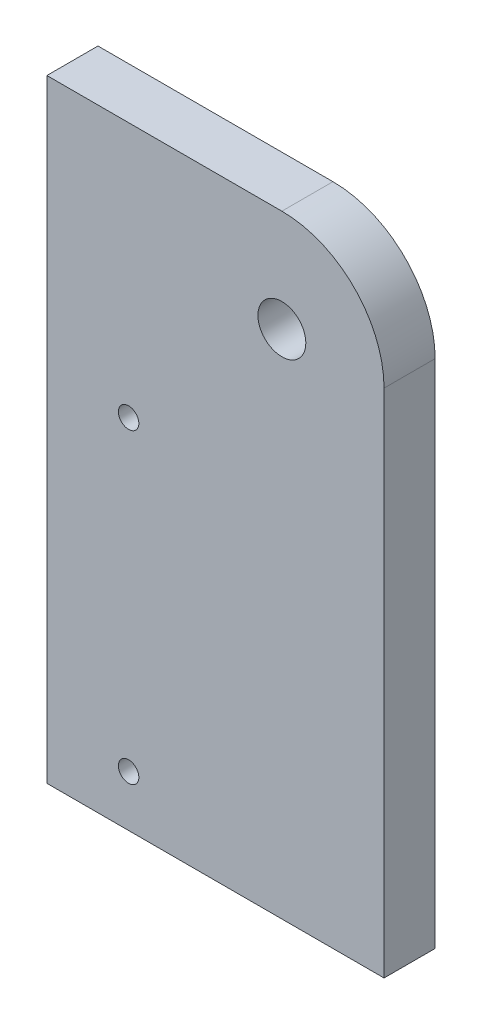
SolidWorks part; units mm, degrees
ref_plane "Alzado" through (0, 0, 0) normal (0, 0, 1) x (1, 0, 0)
ref_plane "Planta" through (0, 0, 0) normal (0, 1, 0) x (1, 0, 0)
ref_plane "Vista lateral" through (0, 0, 0) normal (1, 0, 0) x (0, 0, -1)
sketch "Croquis1" plane through (0, 0, 0) normal (0, 0, 1) x (1, 0, 0)
  line L0 (37.0022, 58.5355) -> (37.0385, 58.5355)
  line L1 (0, 0) -> (33, 0)
  line L2 (0, 0) -> (0, 60)
  line L3 (0, 60) -> (33, 60)
  line L4 (33, 0) -> (33, 60)
  line L5 (33, 60) -> (23, 60)
  line L6 (33, 60) -> (33, 50)
  line L7 (33, 50) -> (23, 50)
  line L8 (23, 60) -> (23, 50)
  circle A0 centre (8, 5) radius 1
  circle A1 centre (8, 35) radius 1
  circle A2 centre (23, 50) radius 2.3438
  arc A3 (23, 60) -> (33, 50) centre (23, 50) cw
  dimension "D2" = 2
  dimension "D3" = 2
  dimension "D10" = 4.6875
  dimension "D1" = 5
  dimension "D4" = 30
  dimension "D5" = 8
  dimension "D6" = 33
  dimension "D7" = 60
  dimension "D8" = 10
  dimension "D9" = 10
extrude "Saliente-Extruir4" add sketch "Croquis1" along normal blind 5 contours A2 L8 L3 L2 L1 L4 L7 A1 A0 | A3 L8 A2 L7
